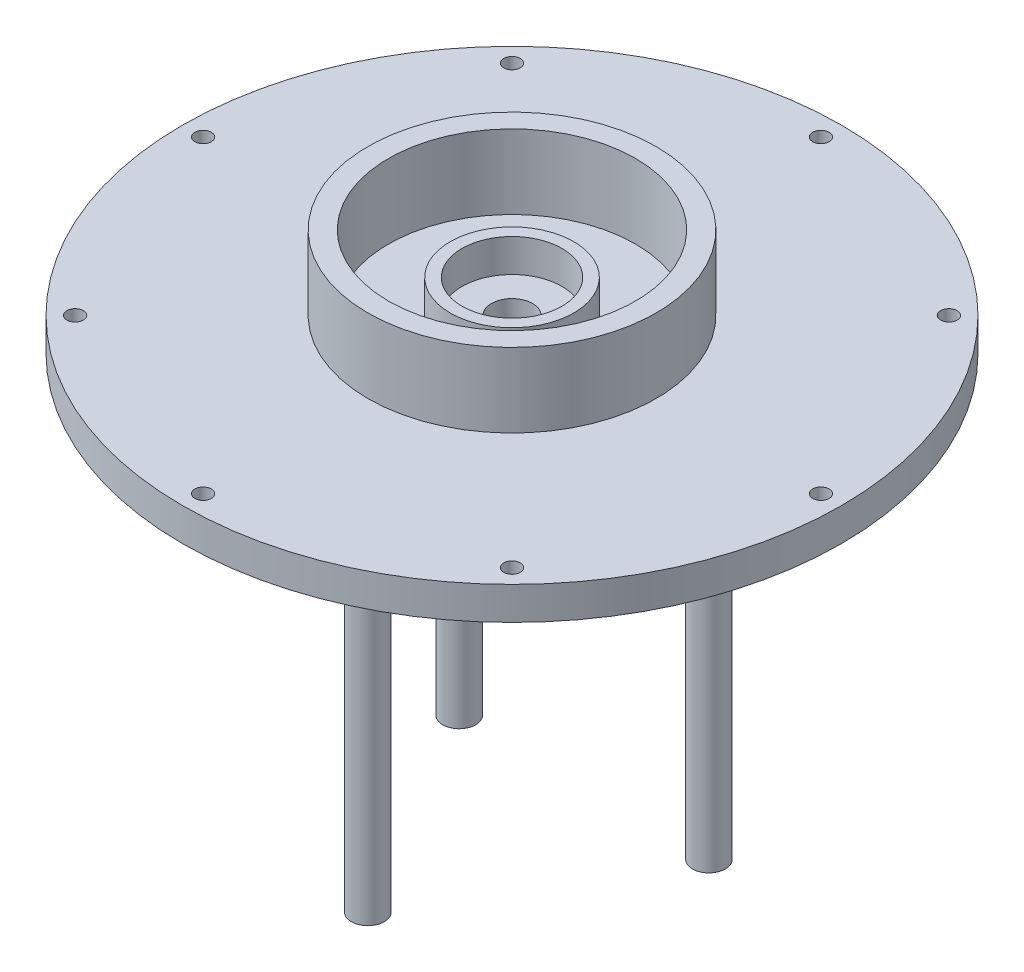
SolidWorks part; units mm, degrees
ref_plane "Alzado" through (0, 0, 0) normal (0, 0, 1) x (1, 0, 0)
ref_plane "Planta" through (0, 0, 0) normal (0, 1, 0) x (1, 0, 0)
ref_plane "Vista lateral" through (0, 0, 0) normal (1, 0, 0) x (0, 0, -1)
sketch "Croquis1" plane through (0, 0, 0) normal (0, 1, 0) x (1, 0, 0)
  circle A0 centre (0, 0) radius 80
  circle A1 centre (0, 0) radius 5
  dimension "D1" = 160
  dimension "D2" = 10
extrude "Saliente-Extruir1" add sketch "Croquis1" along normal blind 8
sketch "Croquis2" plane through (0, 8, 0) normal (0, 1, 0) x (1, 0, 0)
  circle A0 centre (0, 75) radius 2
  circle A1 centre (0, 0) radius 80 construction
  circle A9 centre (53.033, 53.033) radius 2
  circle A10 centre (75, 0) radius 2
  circle A11 centre (53.033, -53.033) radius 2
  circle A12 centre (0, -75) radius 2
  circle A13 centre (-53.033, -53.033) radius 2
  circle A14 centre (-75, 0) radius 2
  circle A15 centre (-53.033, 53.033) radius 2
  point P20 (2.4142, -1)
  point P22 (0, 0)
  dimension "D1" = 4
  dimension "D2" = 75
  dimension "D3" = 8
extrude "Cortar-Extruir1" cut sketch "Croquis2" against normal blind 10
sketch "Croquis3" plane through (0, 8, 0) normal (0, 1, 0) x (1, 0, 0)
  circle A0 centre (0, 0) radius 30
  circle A1 centre (0, 0) radius 35
  circle A2 centre (0, 0) radius 12.15
  circle A5 centre (0, 0) radius 15
  dimension "D1" = 60
  dimension "D2" = 5
  dimension "D3" = 24.3
  dimension "D4" = 30
extrude "Saliente-Extruir2" add sketch "Croquis3" along normal blind 8
sketch "Croquis4" plane through (0, 16, 0) normal (0, 1, 0) x (1, 0, 0)
  circle A0 centre (0, 0) radius 35
  circle A1 centre (0, 0) radius 30
extrude "Saliente-Extruir3" add sketch "Croquis4" along normal blind 10
sketch "Croquis5" plane through (0, 0, 0) normal (0, -1, 0) x (1, 0, 0)
  circle A0 centre (0, 0) radius 35
  circle A1 centre (0, 35) radius 4
  circle A2 centre (30.3109, -17.5) radius 4
  circle A3 centre (-30.3109, -17.5) radius 4
  point P11 (0, 0)
  dimension "D1" = 70
  dimension "D2" = 8
  dimension "D3" = 3
extrude "Saliente-Extruir4" add sketch "Croquis5" along normal blind 100 contours A0 A1 | A0 A2 | A0 A2 | A0 A3
